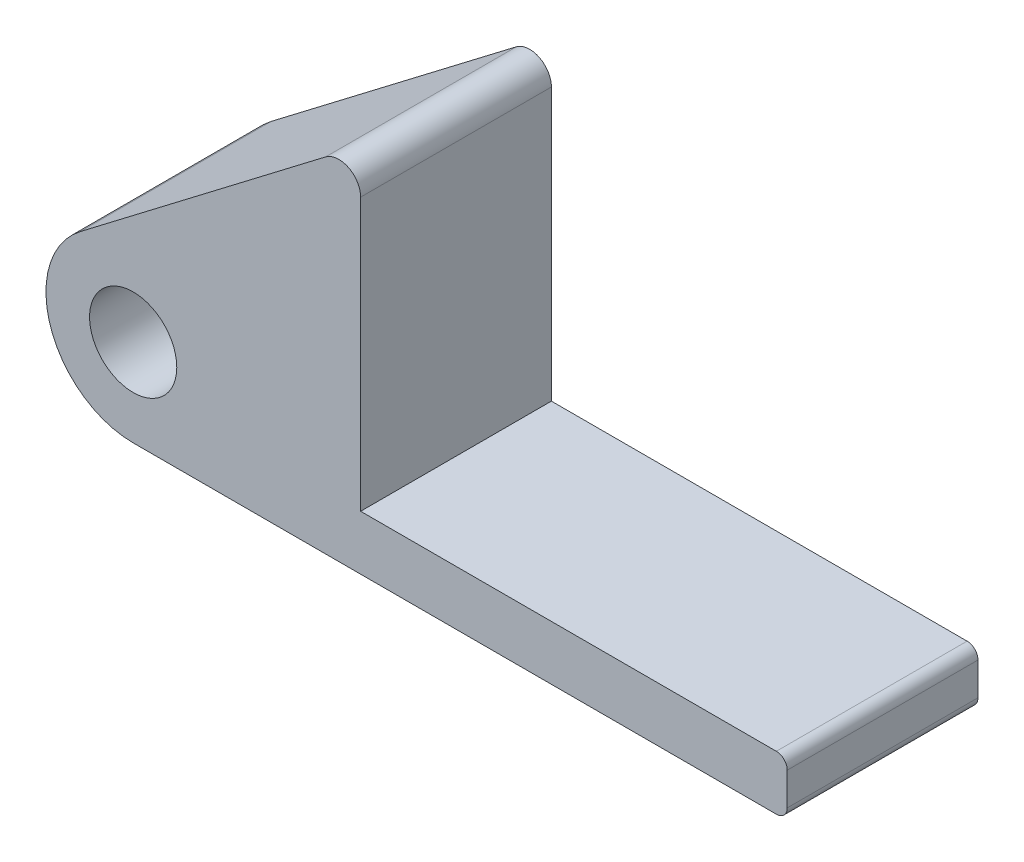
SolidWorks part; units mm, degrees
ref_plane "Plan de face" through (0, 0, 0) normal (0, 0, 1) x (1, 0, 0)
ref_plane "Plan de dessus" through (0, 0, 0) normal (0, 1, 0) x (1, 0, 0)
ref_plane "Plan de droite" through (0, 0, 0) normal (1, 0, 0) x (0, 0, -1)
sketch "Esquisse1" plane through (0, 0, 0) normal (0, 0, 1) x (1, 0, 0)
  line L0 (0, -8) -> (60, -8) construction
  line L1 (60, -8) -> (60, -3) construction
  line L2 (60, -3) -> (20.867, -3) construction
  line L3 (20.867, -3) -> (20.867, 26) construction
  line L4 (20.867, 26) -> (-4.8552, 6.3582) construction
  line L5 (-4.8552, 6.3582) -> (20.867, 26)
  line L6 (20.867, 26) -> (20.867, -3)
  line L7 (20.867, -3) -> (60, -3)
  line L8 (60, -3) -> (60, -8)
  line L9 (60, -8) -> (0, -8)
  circle A0 centre (0, 0) radius 4
  circle A1 centre (0, 0) radius 8
  dimension "D1" = 8
  dimension "D2" = 16
  dimension "D3" = 60
  dimension "D4" = 5
  dimension "D5" = 29
extrude "Boss.-Extru.2" add sketch "Esquisse1" against normal blind 17.5 contours A1 L9 L8 L7 L6 L5 | A1 A0
fillet "Congé1" radius 2 1 edges at (20.867, 26, -8.75)
fillet "Congé2" radius 1 2 edges at (60, -8, -8.75) (60, -3, -8.75)
sketch "Esquisse2" plane through (0, 0, 0) normal (0, 0, 1) x (1, 0, 0)
